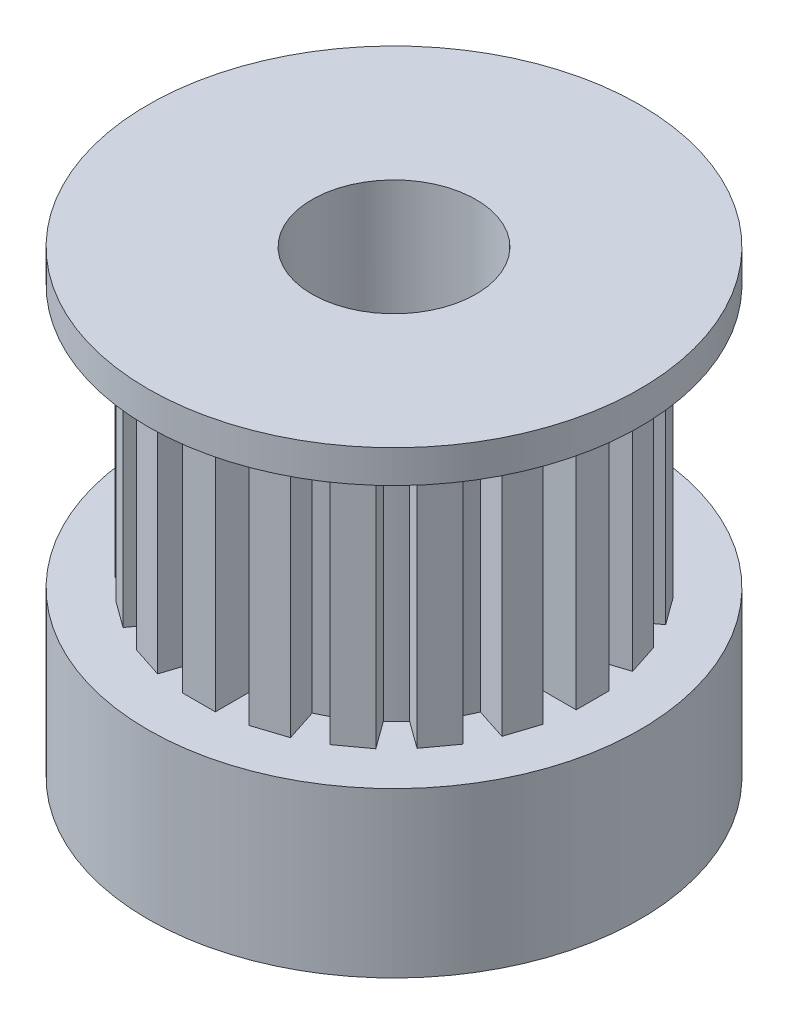
SolidWorks part; units mm, degrees
ref_plane "Ön Düzlem" through (0, 0, 0) normal (0, 0, 1) x (1, 0, 0)
ref_plane "Üst Düzlem" through (0, 0, 0) normal (0, 1, 0) x (1, 0, 0)
ref_plane "Sağ Düzlem" through (0, 0, 0) normal (1, 0, 0) x (0, 0, -1)
sketch "Çizim1" plane through (0, 0, 0) normal (0, 1, 0) x (1, 0, 0)
  circle A0 centre (0, 0) radius 7.5
extrude "Yükseklik-Ekstrüzyon1" add sketch "Çizim1" along normal blind 5
sketch "Çizim6" plane through (0, 5, 0) normal (0, 1, 0) x (1, 0, 0)
  circle A0 centre (0, 0) radius 5
extrude "Yükseklik-Ekstrüzyon5" add sketch "Çizim6" along normal blind 8
sketch "Çizim7" plane through (0, 13, 0) normal (0, 1, 0) x (1, 0, 0)
  line L0 (0, 5) -> (0, 6)
  line L1 (0, 6) -> (0.4468, 6)
  line L2 (0.4468, 6) -> (0.4468, 4.4288)
  line L3 (0.4468, 4.4288) -> (-0.5532, 4.4288)
  line L4 (-0.5532, 4.4288) -> (-0.5532, 6)
  line L5 (-0.5532, 6) -> (0, 6)
  circle A0 centre (0, 0) radius 5 construction
  circle A1 centre (0, 0) radius 5 construction
  circle M3 centre (0, 0) radius 5
extrude "Yükseklik-Ekstrüzyon6" add sketch "Çizim7" against normal blind 8 contours L2 L1 L0 M3 | L5 L4 L0 M3
pattern_circular "Dairesel Kaplama2" count 20 over 360 about axis through (0, 0, 0) along (0, 1, 0) of "Yükseklik-Ekstrüzyon6"
sketch "Çizim8" plane through (0, 13, 0) normal (0, 1, 0) x (1, 0, 0)
  circle A0 centre (0, 0) radius 7.5
extrude "Yükseklik-Ekstrüzyon7" add sketch "Çizim8" along normal blind 1
sketch "Çizim9" plane through (0, 14, 0) normal (0, 1, 0) x (1, 0, 0)
  circle A0 centre (0, 0) radius 2.5
extrude "Kes-Ekstrüzyon2" cut sketch "Çizim9" against normal blind 21
sketch "Çizim10" plane through (0, 0, 0) normal (1, 0, 0) x (0, 0, -1)
  circle A0 centre (0, 2.3612) radius 1.2
extrude "Kes-Ekstrüzyon3" cut sketch "Çizim10" against normal blind 21
